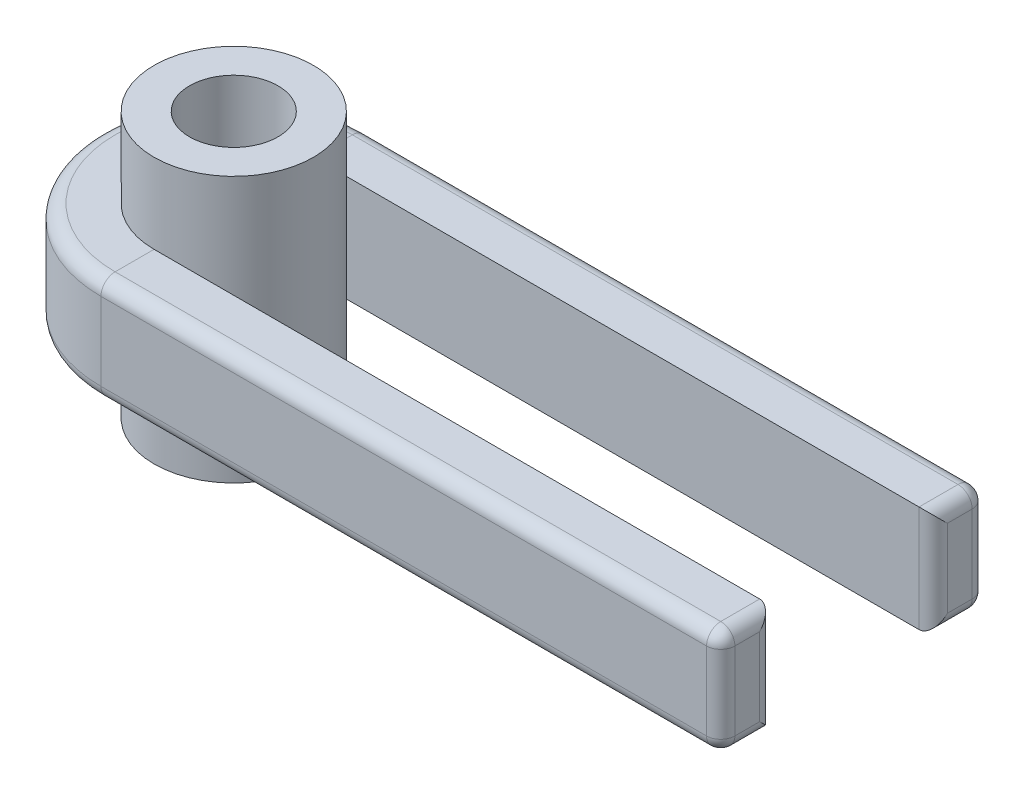
SolidWorks part; units mm, degrees
ref_plane "Front Plane" through (0, 0, 0) normal (0, 0, 1) x (1, 0, 0)
ref_plane "Top Plane" through (0, 0, 0) normal (0, 1, 0) x (1, 0, 0)
ref_plane "Right Plane" through (0, 0, 0) normal (1, 0, 0) x (0, 0, -1)
sketch "Sketch1" plane through (0, 0, 0) normal (0, 1, 0) x (1, 0, 0)
  circle A0 centre (0, 0) radius 4.5
  dimension "D1" = 9
extrude "Boss-Extrude1" add sketch "Sketch1" along normal blind 15
sketch "Sketch2" plane through (0, 15, 0) normal (0, 1, 0) x (1, 0, 0)
  circle A0 centre (0, 0) radius 2.5
  circle A1 centre (0, 0) radius 4.5 construction
  dimension "D1" = 2
extrude "Cut-Extrude1" cut sketch "Sketch2" against normal through all
ref_plane "Plane1" through (0, 7.5, 0) normal (0, 1, 0) x (1, 0, 0)
sketch "Sketch3" plane through (0, 7.5, 0) normal (0, 1, 0) x (1, 0, 0)
  line L0 (0, 6) -> (35, 6)
  line L1 (0, -6) -> (35, -6)
  line L2 (0, 0) -> (0, 6) construction
  line L3 (0, 0) -> (0, -6) construction
  arc A0 (0, 6) -> (0, -6) centre (0, 0) ccw
  dimension "D2" = 6
  dimension "D1" = 35
ref_plane "Plane3" through (0, 0, 0) normal (1, 0, 0) x (0, 0, -1)
ref_plane "Plane4" through (35, 0, 0) normal (1, 0, 0) x (0, 0, -1)
sketch "Sketch4" plane through (35, 0, 0) normal (1, 0, 0) x (0, 0, -1)
  line L1 (4.5, 10.5) -> (7.5, 10.5)
  line L2 (4.5, 10.5) -> (4.5, 4.5)
  line L3 (4.5, 4.5) -> (7.5, 4.5)
  line L4 (7.5, 10.5) -> (7.5, 4.5)
  line L5 (4.5, 10.5) -> (7.5, 4.5) construction
  line L6 (4.5, 4.5) -> (7.5, 10.5) construction
  point P0 (6, 7.5)
  dimension "D1" = 3
  dimension "D2" = 6
sweep "Sweep1" add profiles "Sketch4" path "Sketch3"
fillet "Fillet1" radius 0.8 14 edges at (17.5, 4.5, 7.5) (-7.5, 4.5, 0) (17.5, 10.5, 7.5) (-7.5, 10.5, 0) (35, 10.5, 6) (35, 7.5, 4.5) (35, 4.5, 6) (35, 7.5, 7.5) (35, 4.5, -6) (35, 7.5, -4.5) (35, 10.5, -6) (17.5, 4.5, -7.5) (35, 7.5, -7.5) (17.5, 10.5, -7.5)
